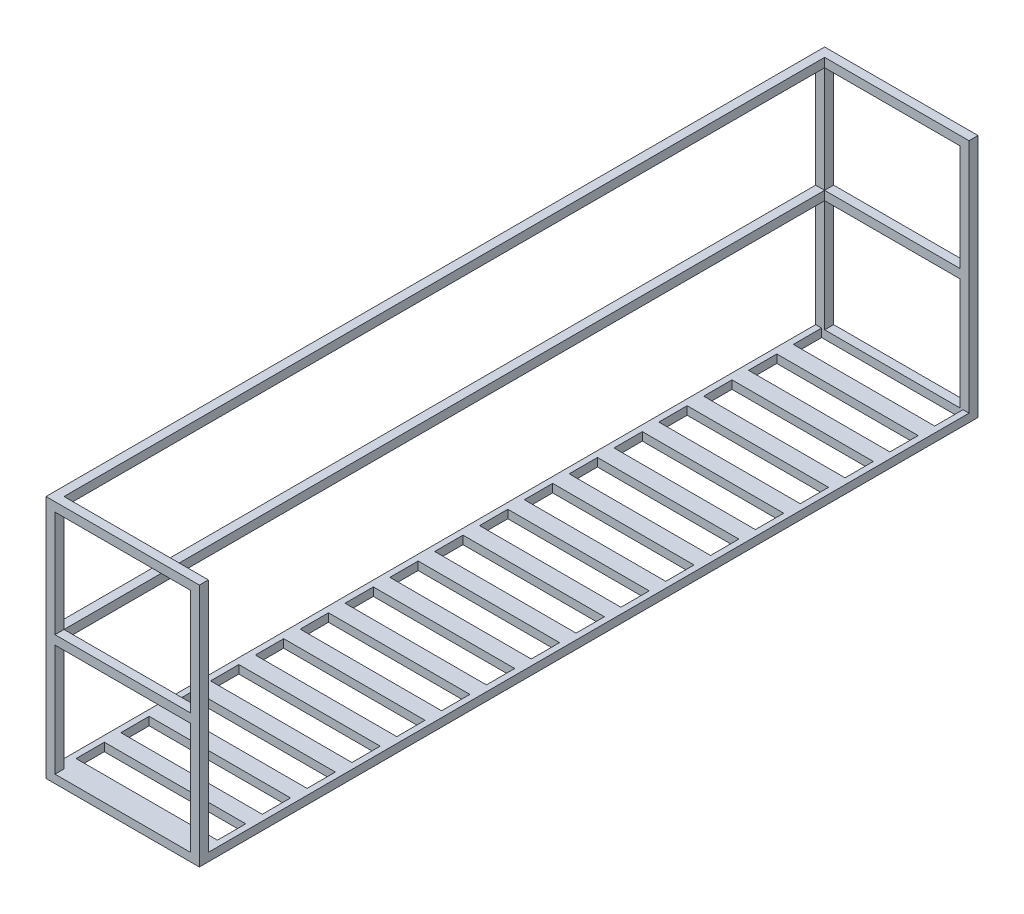
SolidWorks part; units mm, degrees
ref_plane "Alzado" through (0, 0, 0) normal (0, 0, 1) x (1, 0, 0)
ref_plane "Planta" through (0, 0, 0) normal (0, 1, 0) x (1, 0, 0)
ref_plane "Vista lateral" through (0, 0, 0) normal (1, 0, 0) x (0, 0, -1)
sketch "Croquis1" plane through (0, 0, 0) normal (0, 0, 1) x (1, 0, 0)
  line L1 (0, 0) -> (650, 0)
  line L2 (0, 0) -> (0, 35)
  line L3 (0, 35) -> (650, 35)
  line L4 (650, 0) -> (650, 35)
  dimension "D1" = 650
  dimension "D2" = 35
extrude "Saliente-Extruir1" add sketch "Croquis1" along normal blind 3300
sketch "Croquis2" plane through (0, 35, 0) normal (0, 1, 0) x (1, 0, 0)
  line L0 (0, -3300) -> (0, 0) construction
  line L1 (25.4, -38.1) -> (624.6, -38.1)
  line L2 (25.4, -38.1) -> (25.4, -158.1)
  line L3 (25.4, -158.1) -> (624.6, -158.1)
  line L4 (624.6, -38.1) -> (624.6, -158.1)
  line L5 (650, -3300) -> (650, 0) construction
  line L6 (650, 0) -> (0, 0) construction
  dimension "D1" = 25.4
  dimension "D2" = 25.4
  dimension "D3" = 38.1
  dimension "D4" = 120
extrude "Cortar-Extruir1" cut sketch "Croquis2" against normal blind 3000
pattern_linear "MatrizL1" count 17 spacing 190 along (0, 0, 1) of "Cortar-Extruir1"
sketch "Croquis3" plane through (0, 35, 0) normal (0, 1, 0) x (1, 0, 0)
  line L1 (0, -3300) -> (38.1, -3300)
  line L2 (0, -3300) -> (0, -3261.9)
  line L3 (0, -3261.9) -> (38.1, -3261.9)
  line L4 (38.1, -3300) -> (38.1, -3261.9)
  line L5 (650, -3300) -> (611.9, -3300)
  line L6 (650, -3300) -> (650, -3261.9)
  line L7 (650, -3261.9) -> (611.9, -3261.9)
  line L8 (611.9, -3300) -> (611.9, -3261.9)
  line L9 (0, 0) -> (38.1, 0)
  line L10 (0, 0) -> (0, -38.1)
  line L11 (0, -38.1) -> (38.1, -38.1)
  line L12 (38.1, 0) -> (38.1, -38.1)
  line L14 (650, 0) -> (611.9, 0)
  line L15 (650, 0) -> (650, -38.1)
  line L16 (650, -38.1) -> (611.9, -38.1)
  line L17 (611.9, 0) -> (611.9, -38.1)
  dimension "D1" = 38.1
  dimension "D2" = 38.1
  dimension "D3" = 38.1
  dimension "D4" = 38.1
  dimension "D5" = 38.1
  dimension "D6" = 38.1
  dimension "D7" = 38.1
  dimension "D8" = 38.1
extrude "Saliente-Extruir2" add sketch "Croquis3" along normal blind 1000
sketch "Croquis4" plane through (0, 0, 38.1) normal (0, 0, 1) x (1, 0, 0)
  line L0 (0, 1035) -> (0, 35) construction
  line L1 (38.1, 1035) -> (0, 1035)
  line L2 (38.1, 1035) -> (38.1, 996.9)
  line L3 (38.1, 996.9) -> (0, 996.9)
  line L4 (0, 1035) -> (0, 996.9)
  dimension "D1" = 38.1
extrude "Saliente-Extruir3" add sketch "Croquis4" along normal blind 3250
sketch "Croquis5" plane through (0, 0, 38.1) normal (0, 0, 1) x (1, 0, 0)
  line L0 (38.1, 996.9) -> (38.1, 35) construction
  line L1 (38.1, 546.9) -> (0, 546.9)
  line L2 (38.1, 546.9) -> (38.1, 508.8)
  line L3 (38.1, 508.8) -> (0, 508.8)
  line L4 (0, 546.9) -> (0, 508.8)
  line L5 (0, 996.9) -> (0, 35) construction
  line L6 (0, 996.9) -> (38.1, 996.9) construction
  point P10 (19.05, 996.9)
  dimension "D1" = 38.1
  dimension "D2" = 450
extrude "Saliente-Extruir4" add sketch "Croquis5" along normal blind 3250
sketch "Croquis6" plane through (650, 0, 0) normal (1, 0, 0) x (0, 0, -1)
  line L1 (-38.1, 996.9) -> (0, 996.9)
  line L2 (-38.1, 996.9) -> (-38.1, 1035)
  line L3 (-38.1, 1035) -> (0, 1035)
  line L4 (0, 996.9) -> (0, 1035)
extrude "Saliente-Extruir5" add sketch "Croquis6" against normal blind 630
sketch "Croquis7" plane through (650, 0, 0) normal (1, 0, 0) x (0, 0, -1)
  line L1 (-3261.9, 996.9) -> (-3300, 996.9)
  line L2 (-3261.9, 996.9) -> (-3261.9, 1035)
  line L3 (-3261.9, 1035) -> (-3300, 1035)
  line L4 (-3300, 996.9) -> (-3300, 1035)
extrude "Saliente-Extruir6" add sketch "Croquis7" against normal blind 630
sketch "Croquis8" plane through (650, 0, 0) normal (1, 0, 0) x (0, 0, -1)
  line L0 (0, 0) -> (0, 1035) construction
  line L1 (-38.1, 546.9) -> (0, 546.9)
  line L2 (-38.1, 546.9) -> (-38.1, 508.8)
  line L3 (-38.1, 508.8) -> (0, 508.8)
  line L4 (0, 546.9) -> (0, 508.8)
  line L5 (-3300, 0) -> (-3300, 1035) construction
  line L6 (-3261.9, 546.9) -> (-3300, 546.9)
  line L7 (-3261.9, 546.9) -> (-3261.9, 508.8)
  line L8 (-3261.9, 508.8) -> (-3300, 508.8)
  line L9 (-3300, 546.9) -> (-3300, 508.8)
extrude "Saliente-Extruir7" add sketch "Croquis8" against normal blind 630
